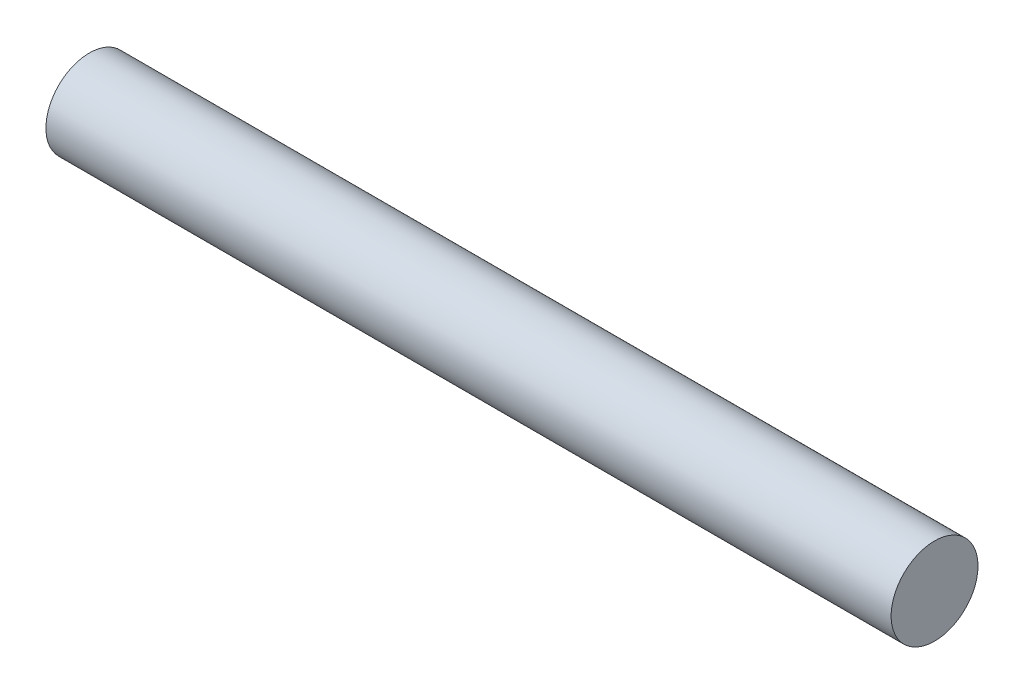
SolidWorks part; units mm, degrees
ref_plane "Front Plane" through (0, 0, 0) normal (0, 0, 1) x (1, 0, 0)
ref_plane "Top Plane" through (0, 0, 0) normal (0, 1, 0) x (1, 0, 0)
ref_plane "Right Plane" through (0, 0, 0) normal (1, 0, 0) x (0, 0, -1)
sketch "Sketch1" plane through (0, 0, 0) normal (1, 0, 0) x (0, 0, -1)
  circle A0 centre (0, 0) radius 0.925
  dimension "D1" = 1.85
extrude "Boss-Extrude1" add sketch "Sketch1" along normal blind 18 contours A0
